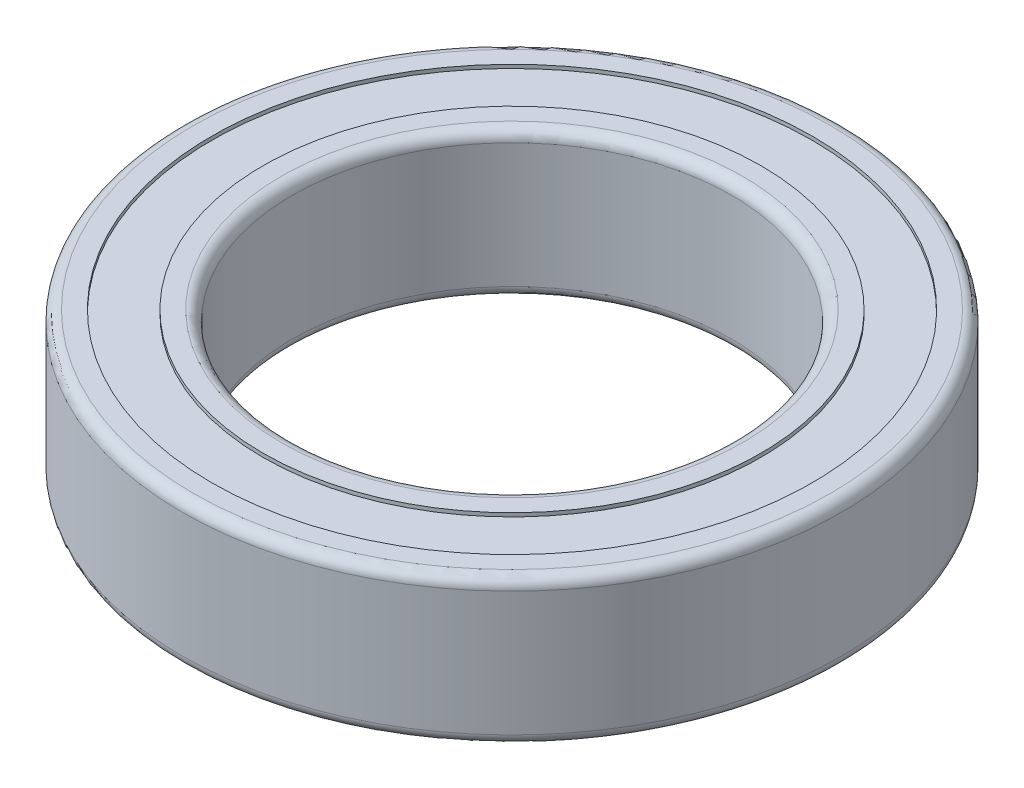
SolidWorks part; units mm, degrees
ref_plane "Alzado" through (0, 0, 0) normal (0, 0, 1) x (1, 0, 0)
ref_plane "Planta" through (0, 0, 0) normal (0, 1, 0) x (1, 0, 0)
ref_plane "Vista lateral" through (0, 0, 0) normal (1, 0, 0) x (0, 0, -1)
sketch "Croquis1" plane through (0, 0, 0) normal (0, 1, 0) x (1, 0, 0)
  circle A0 centre (0, 0) radius 6
  circle A1 centre (0, 0) radius 9
  dimension "D1" = 18
  dimension "D2" = 12
extrude "Saliente-Extruir1" add sketch "Croquis1" along normal blind 4
sketch "Croquis2" plane through (0, 4, 0) normal (0, 1, 0) x (1, 0, 0)
  circle A0 centre (0, 0) radius 8.2
  circle A1 centre (0, 0) radius 6.8
  circle A2 centre (0, 0) radius 6 construction
  circle A3 centre (0, 0) radius 9 construction
  dimension "D1" = 0.8
  dimension "D2" = 0.8
extrude "Cortar-Extruir1" cut sketch "Croquis2" against normal blind 0.1
ref_plane "Plano1" through (0, 2, 0) normal (0, 1, 0) x (1, 0, 0)
mirror "Simetría1" about plane through (0, 2, 0) normal (0, 1, 0) of "Cortar-Extruir1"
fillet "Redondeo1" radius 0.3 4 edges at (0, 0, 9) (0, 4, 9) (0, 0, 6) (0, 4, 6)
